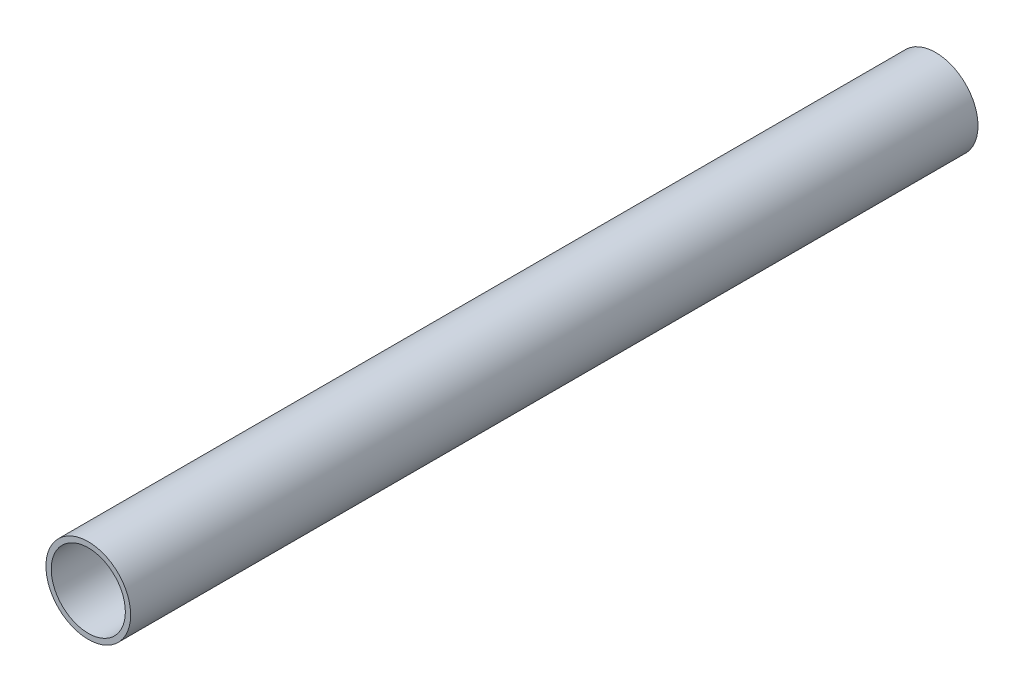
SolidWorks part; units mm, degrees
material "6061-T6 (SS)"
ref_plane "Front Plane" through (0, 0, 0) normal (0, 0, 1) x (1, 0, 0)
ref_plane "Top Plane" through (0, 0, 0) normal (0, 1, 0) x (1, 0, 0)
ref_plane "Right Plane" through (0, 0, 0) normal (1, 0, 0) x (0, 0, -1)
sketch "Sketch2" plane through (0, 0, 0) normal (0, 0, 1) x (1, 0, 0)
  circle A0 centre (0, 0) radius 11.1125
  circle A1 centre (0, 0) radius 12.7
  dimension "D1" = 25.4
  dimension "D2" = 1.5875
extrude "Boss-Extrude1" add sketch "Sketch2" along normal mid plane 254
sketch "Sketch3" plane through (0, 0, 0) normal (0, 1, 0) x (1, 0, 0)
  circle A0 centre (0, 0) radius 2.4892
  dimension "D1" = 4.9784
extrude "Cut-Extrude1" cut sketch "Sketch3" against normal through all
